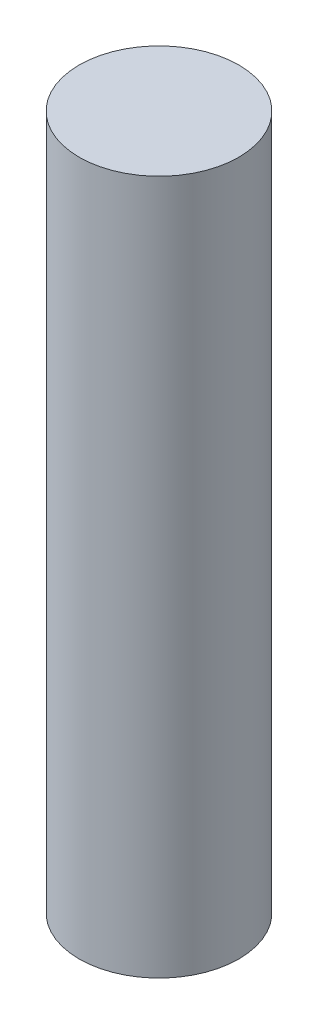
SolidWorks part; units mm, degrees
ref_plane "Front Plane" through (0, 0, 0) normal (0, 0, 1) x (1, 0, 0)
ref_plane "Top Plane" through (0, 0, 0) normal (0, 1, 0) x (1, 0, 0)
ref_plane "Right Plane" through (0, 0, 0) normal (1, 0, 0) x (0, 0, -1)
sketch "Sketch1" plane through (0, 0, 0) normal (0, 1, 0) x (1, 0, 0)
  circle A0 centre (0, 0) radius 3.45
extrude "Boss-Extrude1" add sketch "Sketch1" along normal blind 30
